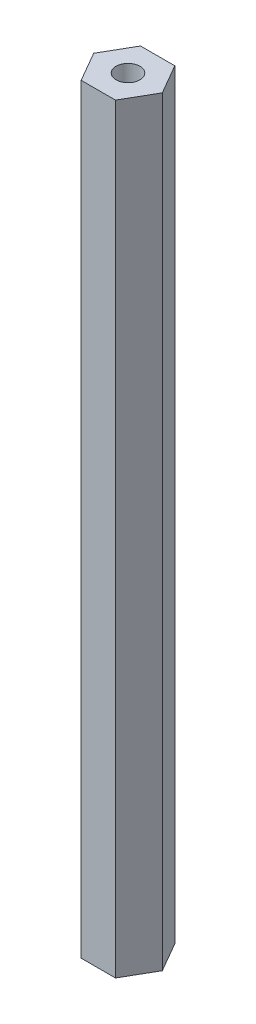
SolidWorks part; units mm, degrees
material "6061-T6 (SS)"
ref_plane "前视基准面" through (0, 0, 0) normal (0, 0, 1) x (1, 0, 0)
ref_plane "上视基准面" through (0, 0, 0) normal (0, 1, 0) x (1, 0, 0)
ref_plane "右视基准面" through (0, 0, 0) normal (1, 0, 0) x (0, 0, -1)
other "Configuration Table"
sketch "草图1" plane through (0, 0, 0) normal (0, 1, 0) x (1, 0, 0)
  line L1 (2.8868, 0) -> (1.4434, 2.5)
  line L2 (1.4434, 2.5) -> (-1.4434, 2.5)
  line L3 (-1.4434, 2.5) -> (-2.8868, 0)
  line L4 (-2.8868, 0) -> (-1.4434, -2.5)
  line L5 (-1.4434, -2.5) -> (1.4434, -2.5)
  line L6 (1.4434, -2.5) -> (2.8868, 0)
  circle A0 centre (0, 0) radius 2.5 construction
  circle A1 centre (0, 0) radius 1
  dimension "D1" = 5
  dimension "D2" = 2
extrude "凸台-拉伸1" add sketch "草图1" along normal blind 64
